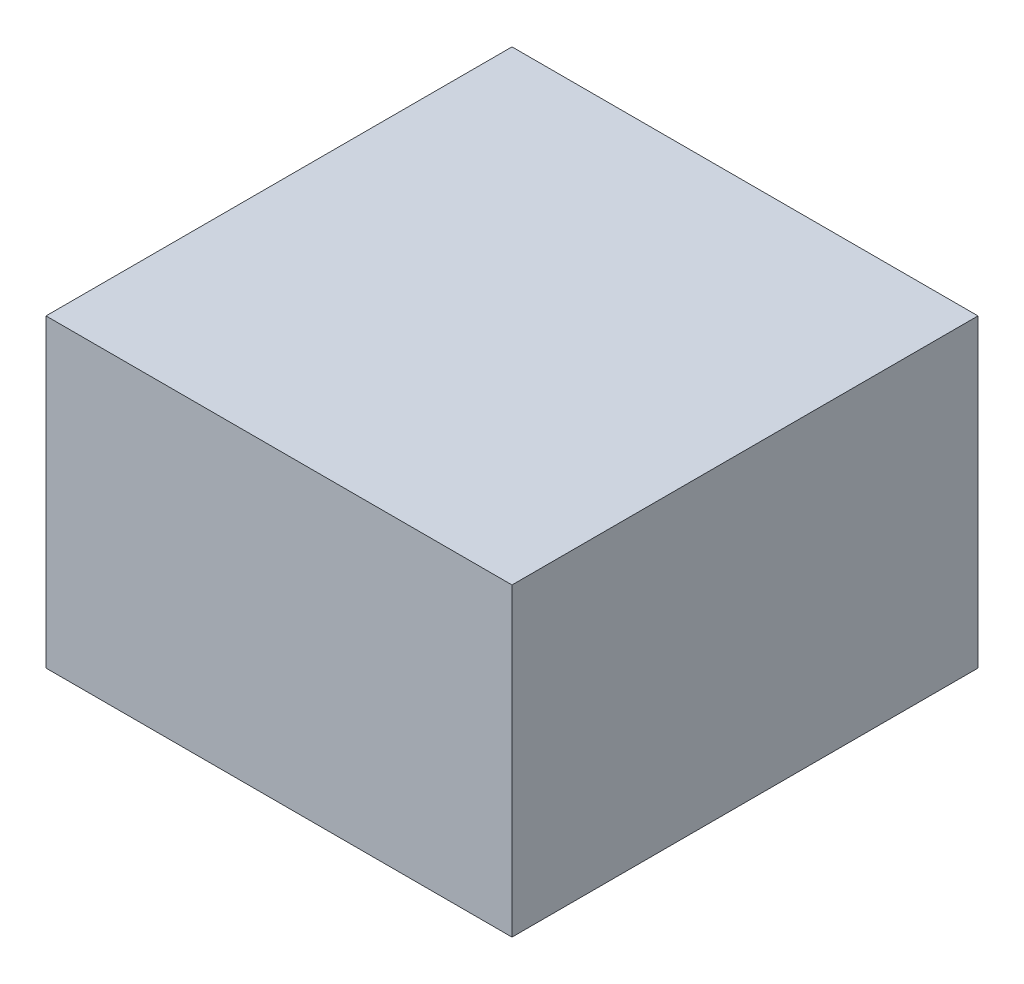
SolidWorks part; units mm, degrees
ref_plane "Front Plane" through (0, 0, 0) normal (0, 0, 1) x (1, 0, 0)
ref_plane "Top Plane" through (0, 0, 0) normal (0, 1, 0) x (1, 0, 0)
ref_plane "Right Plane" through (0, 0, 0) normal (1, 0, 0) x (0, 0, -1)
sketch "Sketch1" plane through (0, 0, 0) normal (0, 1, 0) x (1, 0, 0)
  line L1 (-275, -275) -> (275, -275)
  line L2 (-275, -275) -> (-275, 275)
  line L3 (-275, 275) -> (275, 275)
  line L4 (275, -275) -> (275, 275)
  line L5 (-275, -275) -> (275, 275) construction
  line L6 (-275, 275) -> (275, -275) construction
  point P0 (0, 0)
  dimension "D1" = 550
extrude "Boss-Extrude1" add sketch "Sketch1" along normal blind 360
